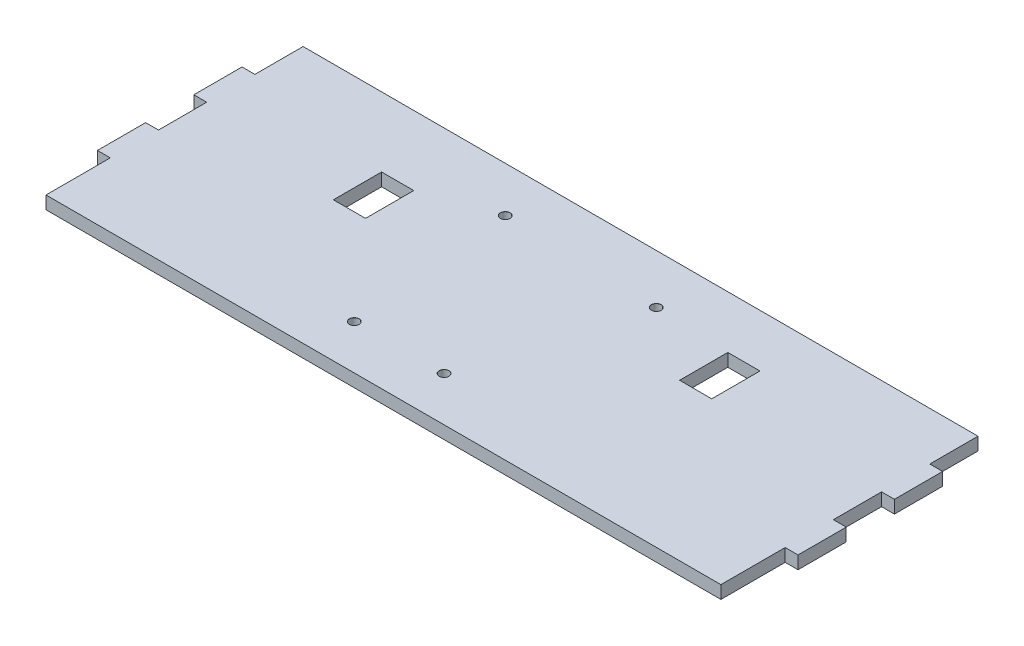
SolidWorks part; units mm, degrees
ref_plane "Front Plane" through (0, 0, 0) normal (0, 0, 1) x (1, 0, 0)
ref_plane "Top Plane" through (0, 0, 0) normal (0, 1, 0) x (1, 0, 0)
ref_plane "Right Plane" through (0, 0, 0) normal (1, 0, 0) x (0, 0, -1)
sketch "Sketch1" plane through (0, 0, 0) normal (0, 1, 0) x (1, 0, 0)
  line L1 (0, 0) -> (210, 0)
  line L2 (0, 0) -> (0, 80)
  line L3 (0, 80) -> (210, 80)
  line L4 (210, 0) -> (210, 80)
  dimension "D1" = 210
  dimension "D2" = 80
extrude "Boss-Extrude1" add sketch "Sketch1" along normal blind 4
sketch "Sketch2" plane through (0, 4, 0) normal (0, 1, 0) x (1, 0, 0)
  line L0 (161.9182, 34.3387) -> (146.9182, 50.3387) construction
  line L1 (158.5091, 63.6418) -> (148.5091, 63.6418)
  line L2 (158.5091, 63.6418) -> (158.5091, 48.6418)
  line L3 (158.5091, 48.6418) -> (148.5091, 48.6418)
  line L4 (148.5091, 63.6418) -> (148.5091, 48.6418)
  line L5 (56.0148, 58.4049) -> (46.0148, 58.4049)
  line L6 (56.0148, 58.4049) -> (56.0148, 43.4049)
  line L7 (56.0148, 43.4049) -> (46.0148, 43.4049)
  line L8 (46.0148, 58.4049) -> (46.0148, 43.4049)
  dimension "D1" = 10
  dimension "D2" = 15
  dimension "D3" = 10
  dimension "D4" = 15
extrude "Cut-Extrude1" cut sketch "Sketch2" against normal through all
sketch "Sketch3" plane through (0, 0, 0) normal (-1, 0, 0) x (0, 0, 1)
  line L0 (-80, 4) -> (0, 4) construction
  line L1 (-65, 4) -> (-50, 4)
  line L2 (-65, 4) -> (-65, 0)
  line L3 (-65, 0) -> (-50, 0)
  line L4 (-50, 4) -> (-50, 0)
  line L5 (-80, 0) -> (0, 0) construction
  line L6 (-80, 4) -> (-80, 0) construction
  line L7 (-35, 4) -> (-20, 4)
  line L8 (-35, 4) -> (-35, 0)
  line L9 (-35, 0) -> (-20, 0)
  line L10 (-20, 4) -> (-20, 0)
  dimension "D1" = 15
  dimension "D2" = 15
  dimension "D3" = 2
extrude "Boss-Extrude2" add sketch "Sketch3" along normal blind 4
sketch "Sketch4" plane through (210, 0, 0) normal (1, 0, 0) x (0, 0, -1)
  line L0 (0, 4) -> (80, 4) construction
  line L1 (65, 4) -> (50, 4)
  line L2 (65, 4) -> (65, 0)
  line L3 (65, 0) -> (50, 0)
  line L4 (50, 4) -> (50, 0)
  line L5 (0, 0) -> (80, 0) construction
  line L6 (80, 4) -> (80, 0) construction
  line L7 (35, 4) -> (20, 4)
  line L8 (35, 4) -> (35, 0)
  line L9 (35, 0) -> (20, 0)
  line L10 (20, 4) -> (20, 0)
  dimension "D1" = 15
  dimension "D2" = 15
  dimension "D3" = 2
extrude "Boss-Extrude3" add sketch "Sketch4" along normal blind 4
hole_wizard "Ø3.0mm Dowel Hole1" positions "Sketch5" profile "Sketch6" hole size "Ø3.0" standard "ISO" end condition through all
sketch "Sketch5" plane through (0, 4, 0) normal (0, 1, 0) x (1, 0, 0)
  point P0 (125.2652, 64.632)
  point P3 (77.0052, 65.902)
  point P6 (82.0852, 13.832)
  point P9 (110.0252, 13.832)
sketch "Sketch6" plane through (125.2652, 4, -64.632) normal (1, 0, 0) x (0, 0, 1)
  line L0 (0, 0) -> (0, 4)
  line L1 (0, 4) -> (1.5, 4)
  line L2 (1.5, 4) -> (1.5, 0.025)
  line L3 (1.5, 0.025) -> (1.525, 0)
  line L5 (1.525, 0) -> (0, 0)
  line L6 (-1.5, 0.025) -> (-1.525, 0) construction
  line L11 (0, -6.35) -> (0, 107.95) construction
  dimension "Thru Hole Dia." = 3
  dimension "Thru Hole Depth" = 4
  dimension "Near C'Sink Dia." = 3.05
  dimension "Near C'Sink Angle" = 90
